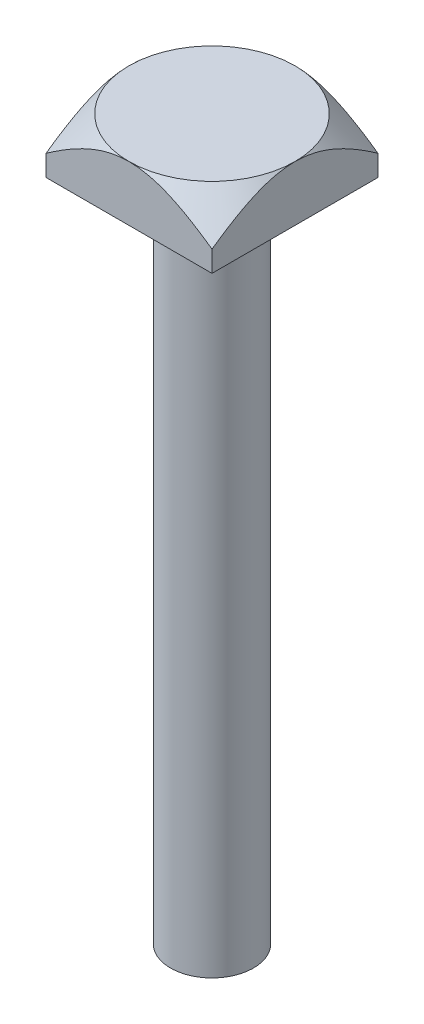
SolidWorks part; units mm, degrees
material "AISI 1045 Steel, cold drawn"
ref_plane "Front Plane" through (0, 0, 0) normal (0, 0, 1) x (1, 0, 0)
ref_plane "Top Plane" through (0, 0, 0) normal (0, 1, 0) x (1, 0, 0)
ref_plane "Right Plane" through (0, 0, 0) normal (1, 0, 0) x (0, 0, -1)
sketch "Sketch1" plane through (0, 0, 0) normal (0, 1, 0) x (1, 0, 0)
  line L1 (-12, 12) -> (12, 12)
  line L2 (-12, 12) -> (-12, -12)
  line L3 (-12, -12) -> (12, -12)
  line L4 (12, 12) -> (12, -12)
  line L5 (0, -12) -> (0, 12) construction
  line L6 (-12, 0) -> (12, 0) construction
  point P0 (0, 0)
  dimension "D1" = 24
  dimension "D2" = 24
extrude "Boss-Extrude1" add sketch "Sketch1" along normal blind 8
sketch "Sketch2" plane through (0, 8, 0) normal (0, 1, 0) x (1, 0, 0)
  circle A0 centre (0, 0) radius 12
  dimension "D1" = 24
extrude "Cut-Extrude1" cut sketch "Sketch2" against normal through all draft 45 flip side to cut
sketch "Sketch3" plane through (0, 0, 0) normal (0, -1, 0) x (1, 0, 0)
  circle A0 centre (0, 0) radius 6
  dimension "D1" = 12
extrude "Boss-Extrude2" add sketch "Sketch3" along normal blind 96
